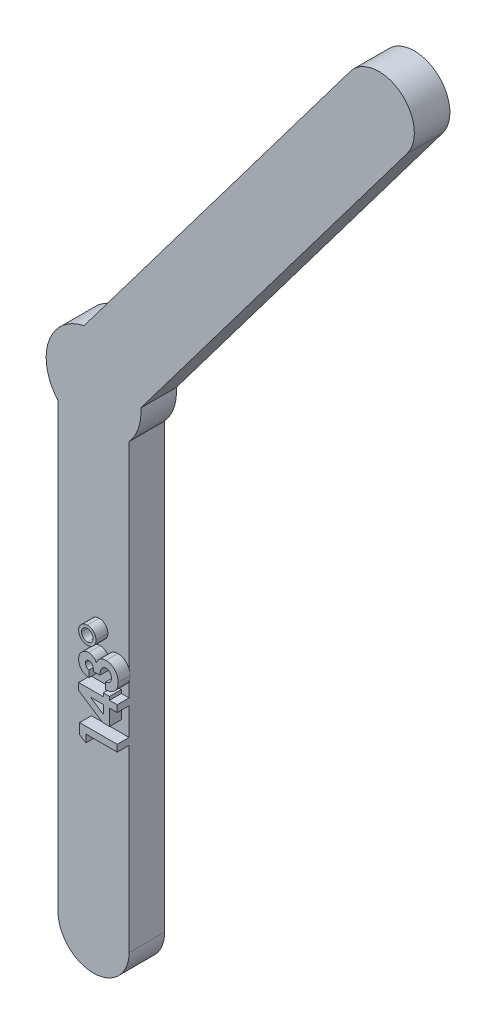
SolidWorks part; units mm, degrees
ref_plane "Front Plane" through (0, 0, 0) normal (0, 0, 1) x (1, 0, 0)
ref_plane "Top Plane" through (0, 0, 0) normal (0, 1, 0) x (1, 0, 0)
ref_plane "Right Plane" through (0, 0, 0) normal (1, 0, 0) x (0, 0, -1)
sketch "Sketch2" plane through (0, 0, 0) normal (0, 0, 1) x (1, 0, 0)
  line L0 (0, 0) -> (0, -40) construction
  line L1 (0, 0) -> (24.0726, 31.9454) construction
  line L2 (21.6767, 33.7509) -> (26.4685, 30.14) construction
  line L3 (-3, -40) -> (3, -40) construction
  line L4 (-3, -40) -> (-3, -2.6458)
  line L5 (3, -40) -> (3, -2.6458)
  line L6 (21.6767, 33.7509) -> (-0.8037, 3.9184)
  line L7 (26.4685, 30.14) -> (3.9882, 0.3075)
  arc A0 (-0.8037, 3.9184) -> (-3, -2.6458) centre (0, 0) ccw
  arc A1 (-3, -40) -> (3, -40) centre (0, -40) ccw
  arc A2 (21.6767, 33.7509) -> (26.4685, 30.14) centre (24.0726, 31.9454) cw
  arc A3 (3, -2.6458) -> (3.9882, 0.3075) centre (0, 0) ccw
  point P12 (24.0726, 31.9454)
  dimension "D3" = 3
  dimension "D4" = 8
  dimension "D1" = 40
  dimension "D2" = 143
extrude "Boss-Extrude1" add sketch "Sketch2" along normal blind 3
sketch "Sketch3" plane through (0, 0, 3) normal (0, 0, 1) x (1, 0, 0)
  text T0 "<b>143°</b>"
extrude "Boss-Extrude2" add sketch "Sketch3" along normal blind 1
